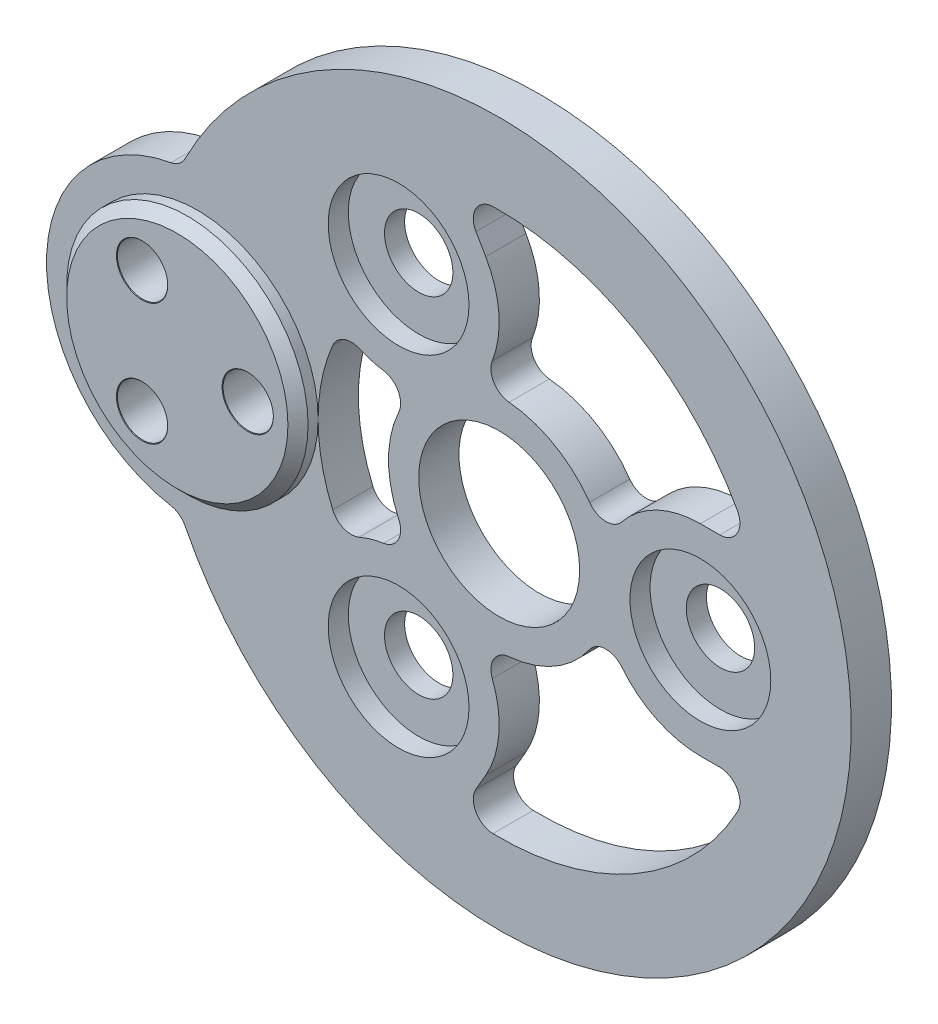
SolidWorks part; units mm, degrees
material "A2017"
ref_plane "正面" through (0, 0, 0) normal (0, 0, 1) x (1, 0, 0)
ref_plane "平面" through (0, 0, 0) normal (0, 1, 0) x (1, 0, 0)
ref_plane "右側面" through (0, 0, 0) normal (1, 0, 0) x (0, 0, -1)
sketch "ｽｹｯﾁ1" plane through (0, 0, 0) normal (0, 0, 1) x (1, 0, 0)
  line L0 (-15, 0) -> (0, 0) construction
  circle A0 centre (0, 0) radius 4
  arc A1 (-4.5, -6) -> (-4.5, 6) centre (0, 0) ccw
  arc A2 (-10.5, 6) -> (-10.5, -6) centre (-15, 0) ccw
  arc A3 (-10.5, 6) -> (-4.5, 6) centre (-7.5, 10) ccw
  arc A4 (-10.5, -6) -> (-4.5, -6) centre (-7.5, -10) cw
  dimension "D1" = 8
  dimension "D2" = 15
  dimension "D3" = 15
  dimension "D4" = 5
extrude "ﾎﾞｽ - 押し出し1" add sketch "ｽｹｯﾁ1" along normal blind 2
sketch "ｽｹｯﾁ6" plane through (0, 0, 2) normal (0, 0, 1) x (1, 0, 0)
  circle A0 centre (-15, 0) radius 6
  dimension "D1" = 12
extrude "ﾎﾞｽ - 押し出し3" add sketch "ｽｹｯﾁ6" along normal blind 1
sketch "ｽｹｯﾁ2" plane through (0, 0, 3) normal (0, 0, 1) x (1, 0, 0)
  circle A0 centre (-15, 0) radius 5 construction
  circle A1 centre (-11.5, 0) radius 1.5 construction
  circle A2 centre (-11.5, 0) radius 0.5
  dimension "D1" = 10
  dimension "D2" = 3
  dimension "D3" = 1
extrude "ｶｯﾄ - 押し出し1" cut sketch "ｽｹｯﾁ2" against normal blind 2
hole_wizard "M3x0.5 ねじ穴1" positions "ｽｹｯﾁ3" profile "ｽｹｯﾁ4" tap size "M3x0.5" standard "JIS" end condition through all
sketch "ｽｹｯﾁ3" plane through (0, 0, 3) normal (0, 0, 1) x (1, 0, 0)
  point P0 (-11.5, 0)
sketch "ｽｹｯﾁ4" plane through (-11.5, 0, 3) normal (1, 0, 0) x (0, -1, 0)
  line L0 (0, 0) -> (0, 3)
  line L1 (0, 3) -> (1.525, 3)
  line L2 (1.25, 2.725) -> (1.25, 0.025)
  line L3 (1.25, 0.025) -> (1.275, 0)
  line L5 (1.275, 0) -> (0, 0)
  line L6 (-1.25, 0.025) -> (-1.275, 0) construction
  line L7 (1.525, 3) -> (1.25, 2.725)
  line L8 (-1.525, 3) -> (-1.25, 2.725) construction
  line L11 (0, -6.35) -> (0, 107.95) construction
  dimension "次ｻｰﾌｪｽまでのねじ下穴ﾄﾞﾘﾙ直径" = 2.5
  dimension "次ｻｰﾌｪｽまでのねじ下穴ﾄﾞﾘﾙの深さ" = 3
  dimension "表面の皿穴の直径" = 2.55
  dimension "表面の皿穴の角度" = 90
  dimension "裏面の皿穴の直径" = 3.05
  dimension "裏面の皿穴の角度" = 90
cosmetic thread "穴のねじ山1" parameters "D2"=3
pattern_circular "円形ﾊﾟﾀｰﾝ1" count 3 over 360 about axis through (-15, 0, 0) along (0, 0, 1) of "M3x0.5 ねじ穴1"
chamfer "面取り1" distance 0.5 angle 45 1 edges at (-9, 0, 3)
chamfer "面取り2" [suppressed] distance 0.5 angle 45
chamfer "面取り3" [suppressed] distance 0.1 angle 45
sketch "ｽｹｯﾁ7" plane through (0, 0, 2) normal (0, 0, 1) x (1, 0, 0)
  circle A0 centre (0, 0) radius 17.5
  arc A5 (-10.5, 6) -> (-4.5, 6) centre (-7.5, 10) ccw
  arc A6 (-10.5, 6) -> (-10.5, -6) centre (-15, 0) ccw
  arc A7 (-4.5, -6) -> (-10.5, -6) centre (-7.5, -10) ccw
  arc A8 (-4.5, -6) -> (-4.5, 6) centre (0, 0) ccw
  arc A9 (-10.5, 6) -> (-4.5, 6) centre (-7.5, 10) ccw
  arc A10 (-10.5, 6) -> (-10.5, -6) centre (-15, 0) ccw
  arc A11 (-4.5, -6) -> (-10.5, -6) centre (-7.5, -10) ccw
  arc A12 (-4.5, -6) -> (-4.5, 6) centre (0, 0) ccw
  circle M5 centre (-15, 0) radius 6
  arc M6 (-4.5, 6) -> (-10.5, 6) centre (-7.5, 10) cw
  arc M7 (-10.5, 6) -> (-10.5, -6) centre (-15, 0) ccw
  arc M8 (-10.5, -6) -> (-4.5, -6) centre (-7.5, -10) cw
  arc M9 (-4.5, -6) -> (-4.5, 6) centre (0, 0) ccw
  circle M10 centre (0, 0) radius 4
  dimension "D1" = 35
  dimension "D2" = 0
extrude "ﾎﾞｽ - 押し出し4" add sketch "ｽｹｯﾁ7" against normal up to surface (2 mm away) contours A0 M7 M6 M9 M8 | A0 M7 M5 M8 M9 M6 M10
hole_wizard "M3 すきま穴1" positions "ｽｹｯﾁ9" profile "ｽｹｯﾁ10" hole size "M3" standard "JIS" end condition through all
sketch "ｽｹｯﾁ9" plane through (0, 0, 2) normal (0, 0, 1) x (1, 0, 0)
  point P0 (-5, 8.6603)
  point P3 (-5, -8.6603)
  point P6 (10, 0)
sketch "ｽｹｯﾁ10" plane through (-5, 8.6603, 2) normal (1, 0, 0) x (0, -1, 0)
  line L0 (0, 0) -> (0, 2)
  line L1 (0, 2) -> (1.7, 2)
  line L2 (1.7, 2) -> (1.7, 0)
  line L5 (1.7, 0) -> (0, 0)
  line L11 (0, -6.35) -> (0, 107.95) construction
  dimension "通し穴の直径" = 3.4
  dimension "通し穴の深さ" = 2
sketch "ｽｹｯﾁ11" plane through (0, 0, 2) normal (0, 0, 1) x (1, 0, 0)
  circle A0 centre (-5, 8.6603) radius 3.5
  circle A1 centre (10, 0) radius 3.5
  circle A2 centre (-5, -8.6603) radius 3.5
  point P11 (0, 0)
  dimension "D1" = 7
  dimension "D2" = 3
extrude "ｶｯﾄ - 押し出し3" cut sketch "ｽｹｯﾁ11" against normal blind 1
sketch "ｽｹｯﾁ12" plane through (0, 0, 2) normal (0, 0, 1) x (1, 0, 0)
  line L0 (10, 0) -> (13.5, 0) construction
  line L1 (10, 5) -> (13.5, 5)
  line L2 (10, -5) -> (13.5, -5)
  line L3 (-5, -8.6603) -> (-6.75, -11.6913) construction
  line L4 (-0.6699, -11.1603) -> (-2.4199, -14.1913)
  line L5 (-9.3301, -6.1603) -> (-11.0801, -9.1913)
  line L6 (-5, 8.6603) -> (-6.75, 11.6913) construction
  line L7 (-9.3301, 6.1603) -> (-11.0801, 9.1913)
  line L8 (-0.6699, 11.1603) -> (-2.4199, 14.1913)
  circle A0 centre (0, 0) radius 13.5
  circle A1 centre (0, 0) radius 5.5
  arc A2 (10, 5) -> (10, -5) centre (10, 0) ccw
  arc A3 (13.5, -5) -> (13.5, 5) centre (13.5, 0) ccw
  arc A4 (-0.6699, -11.1603) -> (-9.3301, -6.1603) centre (-5, -8.6603) ccw
  arc A5 (-11.0801, -9.1913) -> (-2.4199, -14.1913) centre (-6.75, -11.6913) ccw
  arc A6 (-9.3301, 6.1603) -> (-0.6699, 11.1603) centre (-5, 8.6603) ccw
  arc A7 (-2.4199, 14.1913) -> (-11.0801, 9.1913) centre (-6.75, 11.6913) ccw
  arc A8 (-0.3439, 6.8379) -> (0.4969, 5.4775) centre (0.5873, 6.4734) ccw
  arc A9 (4.4952, 3.1691) -> (6.0938, 3.1211) centre (5.3125, 3.7453) ccw
  arc A10 (0.4969, -5.4775) -> (-0.3439, -6.8379) centre (0.5873, -6.4734) ccw
  arc A11 (6.0938, -3.1211) -> (4.4952, -3.1691) centre (5.3125, -3.7453) ccw
  arc A12 (-4.9921, 2.3084) -> (-5.7498, 3.7168) centre (-5.8998, 2.7281) ccw
  arc A13 (-5.7498, -3.7168) -> (-4.9921, -2.3084) centre (-5.8998, -2.7281) ccw
  arc A14 (-7.7884, 4.51) -> (-7.7884, -4.51) centre (0, 0) ccw
  circle A15 centre (-15, 0) radius 6 construction
  point P7 (11.75, 0)
  point P16 (-5.875, -10.1758)
  point P23 (-5.875, 10.1758)
  point P28 (0, 0)
  point P48 (0, 0)
  dimension "D1" = 27
  dimension "D2" = 11
  dimension "D5" = 1
  dimension "D3" = 10
  dimension "D4" = 3
  dimension "D6" = 3
extrude "ｶｯﾄ - 押し出し4" cut sketch "ｽｹｯﾁ12" against normal through all contours A1 A9 A2 L1 A0 L8 A6 A8 | A2 A11 A1 A10 A4 L4 A0 L2 | A6 A14 A4 A13 A1 A12
fillet "ﾌｨﾚｯﾄ1" radius 1 6 edges at (12.5399, -5, 1) (-1.9398, -13.3599, 1) (12.5399, 5, 1) (-7.7884, -4.51, 1) (-7.7884, 4.51, 1) (-1.9398, 13.3599, 1)
fillet "ﾌｨﾚｯﾄ2" radius 1 2 edges at (-15.8333, -7.4536, 1) (-15.8333, 7.4536, 1)
